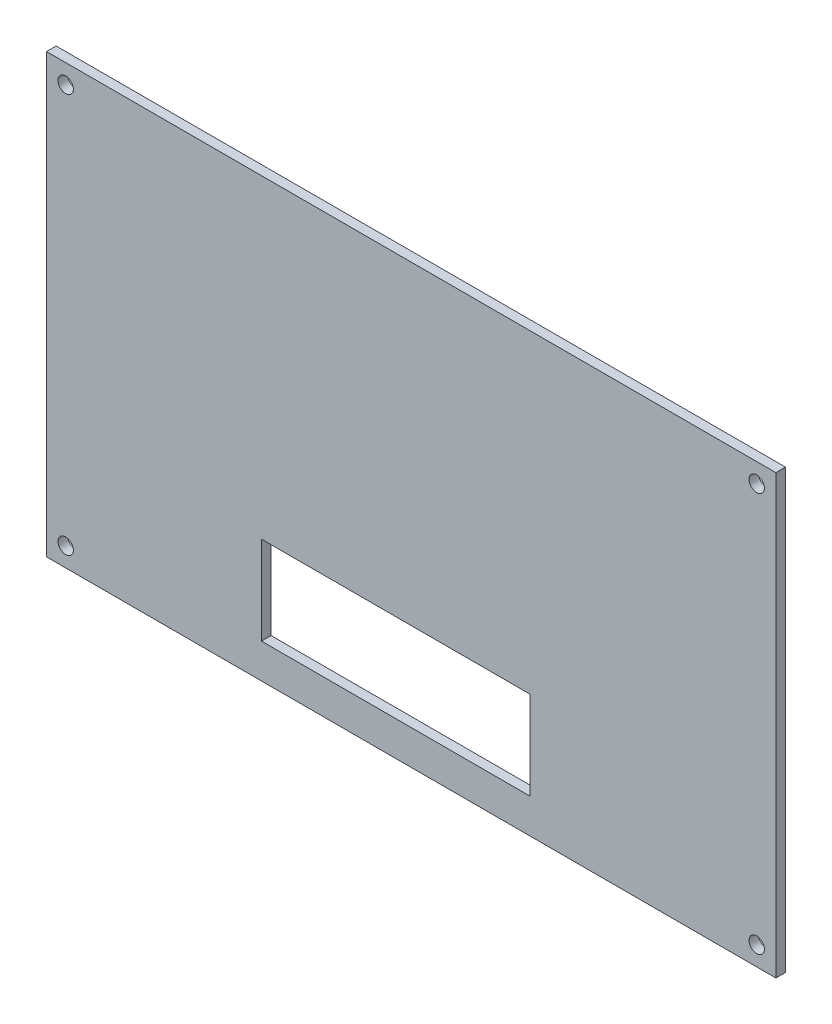
SolidWorks part; units mm, degrees
ref_plane "Front Plane" through (0, 0, 0) normal (0, 0, 1) x (1, 0, 0)
ref_plane "Top Plane" through (0, 0, 0) normal (0, 1, 0) x (1, 0, 0)
ref_plane "Right Plane" through (0, 0, 0) normal (1, 0, 0) x (0, 0, -1)
sketch "Sketch1" plane through (0, 0, 0) normal (0, 0, 1) x (1, 0, 0)
  line L1 (-95, -57) -> (95, -57)
  line L2 (-95, -57) -> (-95, 57)
  line L3 (-95, 57) -> (95, 57)
  line L4 (95, -57) -> (95, 57)
  line L5 (-95, -57) -> (95, 57) construction
  line L6 (-95, 57) -> (95, -57) construction
  point P0 (0, 0)
  dimension "D1" = 190
  dimension "D2" = 114
extrude "Boss-Extrude1" add sketch "Sketch1" along normal blind 2.5
sketch "Sketch2" plane through (0, 0, 2.5) normal (0, 0, 1) x (1, 0, 0)
  text T0 "LEFT" font "Century Gothic" height in points 72
extrude "Cut-Extrude1" [suppressed] cut sketch "Sketch2" against normal blind 1
sketch "Sketch3" plane through (0, 0, 2.5) normal (0, 0, 1) x (1, 0, 0)
  line L0 (95, -57) -> (95, 57) construction
  line L1 (-39, -25) -> (31, -25)
  line L2 (-39, -25) -> (-39, -48)
  line L3 (-39, -48) -> (31, -48)
  line L4 (31, -25) -> (31, -48)
  line L5 (-39, -25) -> (31, -48) construction
  line L6 (-39, -48) -> (31, -25) construction
  line L8 (-95, -57) -> (95, -57) construction
  point P0 (-4, -36.5)
  dimension "D1" = 70
  dimension "D2" = 23
  dimension "D3" = 64
  dimension "D4" = 32
extrude "Cut-Extrude2" cut sketch "Sketch3" against normal blind 10
sketch "Sketch4" plane through (0, 0, 2.5) normal (0, 0, 1) x (1, 0, 0)
  line L0 (95, 57) -> (-95, 57) construction
  line L1 (-95, 57) -> (-95, -57) construction
  line L3 (0, -1000) -> (0, 49000) construction
  line L5 (-95, -57) -> (95, -57) construction
  circle A0 centre (-90, 52) radius 2
  circle A3 centre (90, 52) radius 2
  circle A4 centre (-90, -52) radius 2
  circle A5 centre (90, -52) radius 2
  dimension "D1" = 4
  dimension "D2" = 5
  dimension "D3" = 5
  dimension "D4" = 4
  dimension "D5" = 5
  dimension "D6" = 5
extrude "Cut-Extrude3" cut sketch "Sketch4" against normal blind 10
